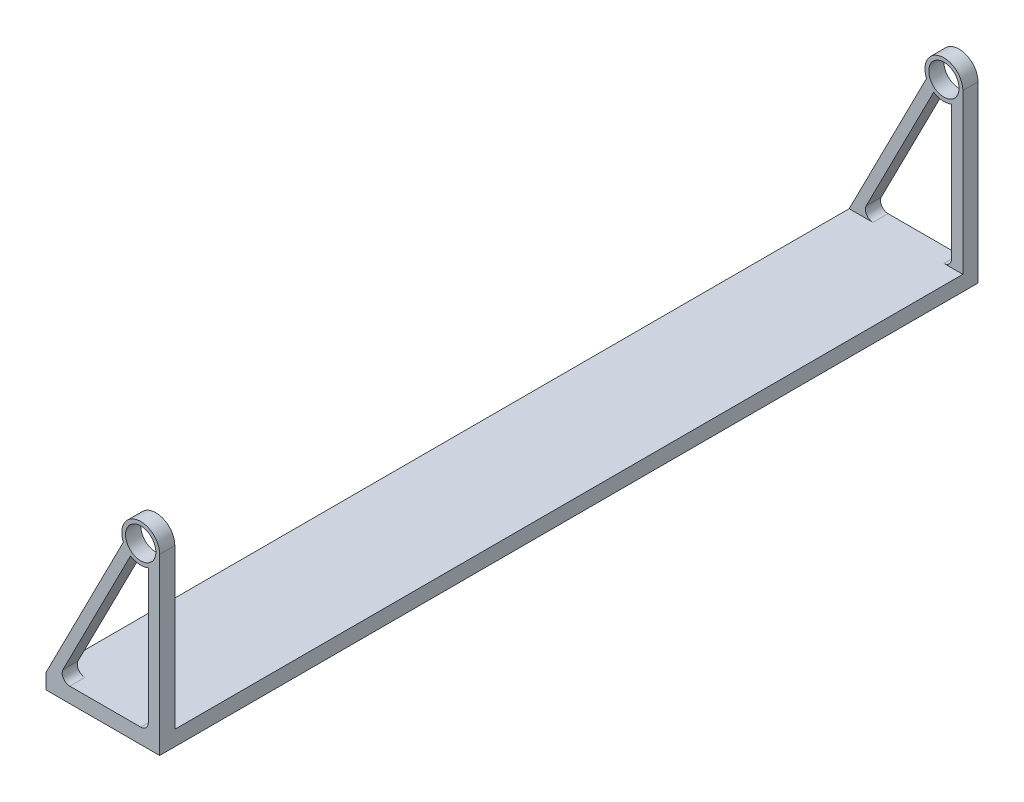
SolidWorks part; units mm, degrees
ref_plane "Front Plane" through (0, 0, 0) normal (0, 0, 1) x (1, 0, 0)
ref_plane "Top Plane" through (0, 0, 0) normal (0, 1, 0) x (1, 0, 0)
ref_plane "Right Plane" through (0, 0, 0) normal (1, 0, 0) x (0, 0, -1)
sketch "Sketch1" plane through (0, 0, 0) normal (0, 1, 0) x (1, 0, 0)
  line L1 (-190.5, -1371.6) -> (190.5, -1371.6)
  line L2 (-190.5, -1371.6) -> (-190.5, 1371.6)
  line L3 (-190.5, 1371.6) -> (190.5, 1371.6)
  line L4 (190.5, -1371.6) -> (190.5, 1371.6)
  line L5 (-190.5, -1371.6) -> (190.5, 1371.6) construction
  line L6 (-190.5, 1371.6) -> (190.5, -1371.6) construction
  point P0 (0, 0)
  dimension "D1" = 381
  dimension "D2" = 2743.2
extrude "Boss-Extrude1" add sketch "Sketch1" along normal blind 50.8
ref_plane "Plane1" through (0, 0, 1371.6) normal (0, 0, 1) x (1, 0, 0)
sketch "Sketch2" plane through (0, 0, 1371.6) normal (0, 0, 1) x (1, 0, 0)
  line L0 (190.5, 50.8) -> (190.5, 584.2)
  line L1 (190.5, 50.8) -> (152.4, 50.8)
  line L2 (-190.5, 50.8) -> (190.5, 50.8) construction
  line L3 (152.4, 50.8) -> (152.4, 526.0013)
  line L4 (-190.5, 50.8) -> (68.8989, 558.5774)
  line L5 (-190.5, 50.8) -> (-152.4, 50.8)
  line L6 (-152.4, 50.8) -> (92.7668, 530.7178)
  circle A0 centre (127, 584.2) radius 63.5
  circle A1 centre (127, 584.2) radius 50.8
  dimension "D2" = 127
  dimension "D3" = 101.6
  dimension "D1" = 533.4
  dimension "D4" = 38.1
  dimension "D5" = 38.1
extrude "Boss-Extrude2" add sketch "Sketch2" against normal blind 50.8 contours A0 L4 L5 L6 | A0 L3 L1 L0 | A0 A1
mirror "Mirror1" about plane through (0, 0, 0) normal (0, 0, 1) of "Boss-Extrude2"
fillet "Fillet1" radius 25.4 4 edges at (152.4, 50.8, -1346.2) (-152.4, 50.8, -1346.2) (-152.4, 50.8, 1346.2) (152.4, 50.8, 1346.2)
